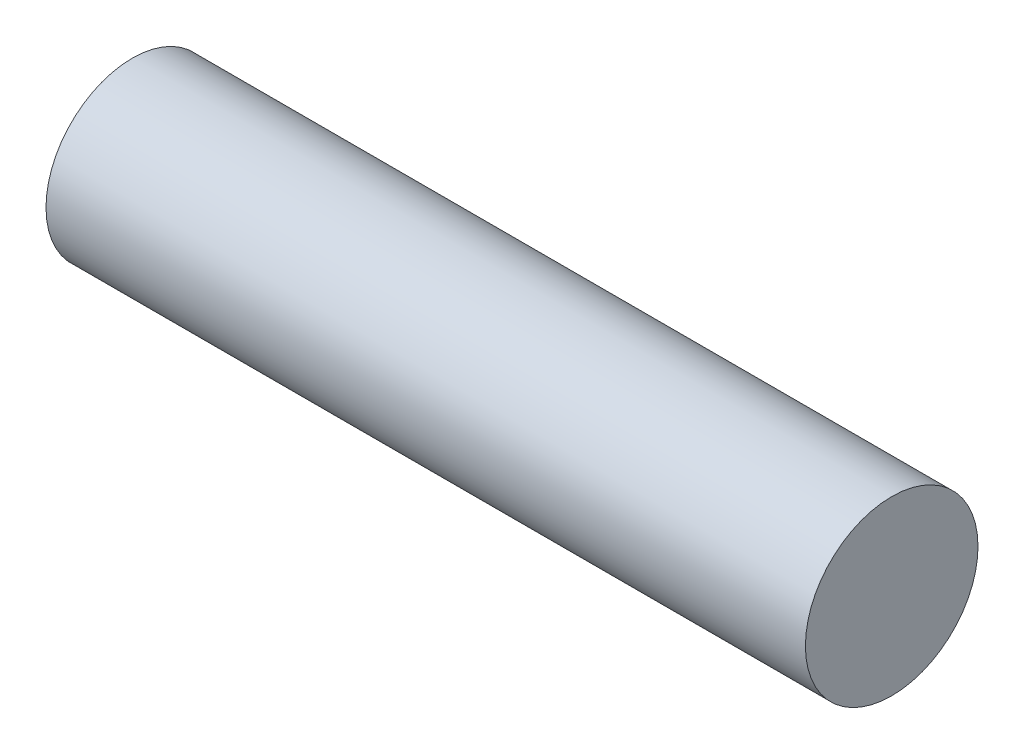
SolidWorks part; units mm, degrees
ref_plane "Front Plane" through (0, 0, 0) normal (0, 0, 1) x (1, 0, 0)
ref_plane "Top Plane" through (0, 0, 0) normal (0, 1, 0) x (1, 0, 0)
ref_plane "Right Plane" through (0, 0, 0) normal (1, 0, 0) x (0, 0, -1)
sketch "Эскиз1" plane through (0, 0, 0) normal (1, 0, 0) x (0, 0, -1)
  circle A0 centre (0, 0) radius 5
  dimension "D1" = 10
extrude "Бобышка-Вытянуть1" add sketch "Эскиз1" along normal blind 44
